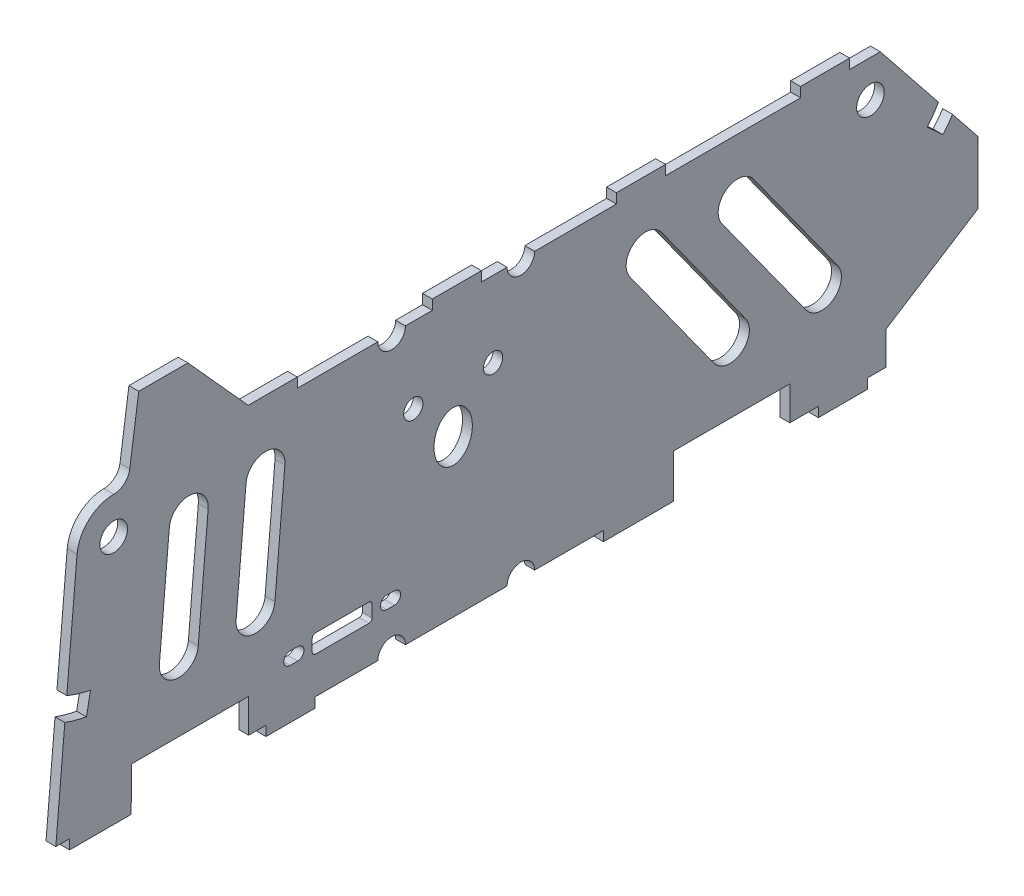
SolidWorks part; units mm, degrees
ref_plane "前视基准面" through (0, 0, 0) normal (0, 0, 1) x (1, 0, 0)
ref_plane "上视基准面" through (0, 0, 0) normal (0, 1, 0) x (1, 0, 0)
ref_plane "右视基准面" through (0, 0, 0) normal (1, 0, 0) x (0, 0, -1)
sketch "右侧结构" plane through (0, 0, 0) normal (1, 0, 0) x (0, 0, -1)
  line L0 (-44.2613, 14.3381) -> (-20.3822, 14.3381) construction
  line L1 (-96.6617, 0) -> (38.5883, 0)
  line L6 (-44.2613, 18.3959) -> (-20.3822, 18.3959) construction
  line L8 (-44.2613, 18.3959) -> (-44.2613, 16.3959) construction
  line L9 (-44.2613, 12.3381) -> (-20.3822, 12.3381) construction
  line L10 (-20.3822, 12.3381) -> (-20.3822, 14.3381) construction
  line L11 (-44.2613, 16.3959) -> (-20.3822, 16.3959) construction
  line L12 (-44.2613, 14.3381) -> (-44.2613, 12.3381) construction
  line L13 (-20.3822, 16.3959) -> (-20.3822, 18.3959) construction
  line L16 (-19.1356, 10.5554) -> (-5.2617, 10.5554) construction
  line L17 (-5.2617, 10.5554) -> (-5.2617, 14.5) construction
  line L18 (-5.2617, 14.5) -> (-19.1356, 14.5) construction
  line L19 (-19.1356, 14.5) -> (-19.1356, 10.5554) construction
  line L21 (36.0883, 39) -> (47.8781, 28.2124) construction
  line L22 (37.6933, 45) -> (-87.2267, 45)
  line L23 (-93.2039, 39.5229) -> (-96.6617, 0) construction
  line L25 (38.5883, 0) -> (38.5883, 43.8804) construction
  line L26 (38.5883, 43.8804) -> (37.6933, 45) construction
  line L36 (45.3288, 30.545) -> (47.8781, 28.2124)
  line L39 (-87.2267, 39) -> (-91.6701, 15.8134) construction
  line L42 (-91.0113, 19.2508) -> (-91.6701, 15.8134)
  line L45 (-93.2039, 39.5229) -> (-94.8767, 20.4034)
  line L57 (38.5883, 43.8804) -> (53.614, 25.0824) construction
  line L60 (53.614, 25.0824) -> (53.614, 14.8778)
  line L66 (38.5883, 5.3637) -> (38.5883, 0)
  line L88 (37.6933, 45) -> (47.164, 33.1517)
  line L97 (42.0237, 27.9708) -> (34.3307, 37.5952) construction
  line L107 (49.4706, 30.266) -> (53.614, 25.0824)
  line L108 (53.614, 14.8778) -> (38.5883, 5.3637)
  line L109 (42.0237, 27.9708) -> (44.209, 25.2369) construction
  line L110 (-95.194, 16.7764) -> (-96.6617, 0)
  arc A0 (-87.2267, 45) -> (-93.2039, 39.5229) centre (-87.2267, 39) ccw
  circle A21 centre (36.0883, 39) radius 2.25
  arc A23 (47.164, 33.1517) -> (42.0237, 27.9708) centre (36.0883, 39) cw construction
  arc A24 (49.4706, 30.266) -> (44.209, 25.2369) centre (36.0883, 39) cw construction
  arc A25 (47.164, 33.1517) -> (45.3288, 30.545) centre (36.0883, 39) cw
  arc A28 (49.4706, 30.266) -> (47.8781, 28.2124) centre (36.0883, 39) cw
  circle A31 centre (-87.2267, 39) radius 2.25
  arc A32 (-94.8767, 20.4034) -> (-91.0113, 19.2508) centre (-87.2267, 39) ccw
  arc A33 (-95.194, 16.7764) -> (-91.6701, 15.8134) centre (-87.2267, 39) ccw
  arc A34 (-44.1822, 45) -> (-39.6822, 45) centre (-41.9322, 45) ccw
  arc A35 (-23.1322, 45) -> (-18.6322, 45) centre (-20.8822, 45) ccw
  arc A37 (-44.1822, 0) -> (-39.6822, 0) centre (-41.9322, 0) cw
  arc A38 (-23.1322, 0) -> (-18.6322, 0) centre (-20.8822, 0) cw
  dimension "D1" = 6
  dimension "D3" = 12.3381
  dimension "D11" = 135.25
  dimension "D13" = 4.5
  dimension "D14" = 6
  dimension "D19" = 3.5
  dimension "D20" = 2.25
  dimension "D2" = 45
  dimension "D4" = 1.7827
  dimension "D5" = 3.9446
  dimension "D6" = 23.8791
  dimension "D7" = 13.8739
  dimension "D8" = 1.2466
  dimension "D9" = 2.0578
  dimension "D10" = 2
  dimension "D12" = 85
  dimension "D15" = 43.85
  dimension "D16" = 3.5
  dimension "D17" = 5
  dimension "D18" = 2.5
  dimension "D21" = 21.55
  dimension "D22" = 0.5
extrude "凸台-拉伸1" add sketch "右侧结构" along normal blind 1.6
sketch "草图2" plane through (0, 0, 0) normal (1, 0, 0) x (0, 0, -1)
  line L0 (35.5883, 0) -> (35.5883, -1.6)
  line L1 (-83.1502, 57.5) -> (-84.6077, 47.2723)
  line L2 (35.5883, -1.6) -> (27.5883, -1.6)
  line L3 (27.5883, -1.6) -> (27.5883, 0)
  line L4 (27.5883, 0) -> (35.5883, 0)
  line L5 (-83.1502, 57.5) -> (-75.1391, 57.5)
  line L6 (-2.4117, 0) -> (5.5883, 0)
  line L7 (5.5883, 0) -> (5.5883, -1.6)
  line L8 (5.5883, -1.6) -> (-2.4117, -1.6)
  line L9 (-2.4117, -1.6) -> (-2.4117, 0)
  line L10 (-32.4117, 0) -> (-24.4117, 0) construction
  line L11 (-24.4117, 0) -> (-24.4117, -1.6) construction
  line L12 (-24.4117, -1.6) -> (-32.4117, -1.6) construction
  line L13 (-32.4117, -1.6) -> (-32.4117, 0) construction
  line L14 (-62.4117, 0) -> (-54.4117, 0)
  line L15 (-54.4117, 0) -> (-54.4117, -1.6)
  line L16 (-54.4117, -1.6) -> (-62.4117, -1.6)
  line L17 (-62.4117, -1.6) -> (-62.4117, 0)
  line L18 (-92.4117, 0) -> (-84.4117, 0)
  line L19 (-84.4117, 0) -> (-84.4117, -1.6)
  line L20 (-84.4117, -1.6) -> (-92.4117, -1.6)
  line L21 (-92.4117, -1.6) -> (-92.4117, 0)
  line L22 (32.6933, 46.6) -> (32.6933, 45)
  line L23 (32.6933, 45) -> (24.6933, 45)
  line L24 (24.6933, 45) -> (24.6933, 46.6)
  line L25 (24.6933, 46.6) -> (32.6933, 46.6)
  line L26 (-75.1391, 57.5) -> (-65.3067, 46.6)
  line L27 (2.6933, 46.6) -> (2.6933, 45)
  line L28 (2.6933, 45) -> (-5.3067, 45)
  line L29 (-5.3067, 45) -> (-5.3067, 46.6)
  line L30 (-5.3067, 46.6) -> (2.6933, 46.6)
  line L31 (-27.3067, 46.6) -> (-27.3067, 45)
  line L32 (-27.3067, 45) -> (-35.3067, 45)
  line L33 (-35.3067, 45) -> (-35.3067, 46.6)
  line L34 (-35.3067, 46.6) -> (-27.3067, 46.6)
  line L35 (-57.3067, 46.6) -> (-57.3067, 45)
  line L36 (-57.3067, 45) -> (-65.3067, 45)
  line L37 (-65.3067, 45) -> (-65.3067, 46.6) construction
  line L38 (-65.3067, 46.6) -> (-57.3067, 46.6)
  line L39 (38.5883, 5.3637) -> (38.5883, 0) construction
  line L40 (-18.6322, 0) -> (38.5883, 0) construction
  line L41 (37.6933, 45) -> (-18.6322, 45) construction
  line L42 (-87.2267, 45) -> (-65.3067, 45)
  arc A0 (-87.2267, 45) -> (-84.6077, 47.2723) centre (-87.2267, 47.6455) ccw
  dimension "D1" = 3
  dimension "D2" = 1.6
  dimension "D3" = 8
  dimension "D5" = 1.6
  dimension "D6" = 8
  dimension "D7" = 5
  dimension "D9" = 12.5
  dimension "D4" = 5
  dimension "D8" = 4
extrude "上下板接口" add sketch "草图2" along normal up to surface (1.6 mm away) from surface at 0 up to face at (1.6, 39, 84.9767) starting at face at (0, 39, 84.9767)
sketch "Sketch2" plane through (1.6, 0, 0) normal (1, 0, 0) x (0, 0, -1)
  line L0 (-84.3141, 0) -> (-84.3141, 5.5)
  line L1 (-84.4117, 0) -> (-62.4117, 0) construction
  line L2 (-84.3141, 5.5) -> (-65.2413, 5.5)
  line L3 (-65.2413, 5.5) -> (-65.2413, 0)
  line L4 (-65.2413, 0) -> (-84.3141, 0)
  line L5 (3.9897, 0) -> (3.9897, 5.5)
  line L6 (5.5883, 0) -> (27.5883, 0) construction
  line L7 (3.9897, 5.5) -> (22.9457, 5.5)
  line L8 (22.9457, 5.5) -> (22.9457, 0)
  line L9 (22.9457, 0) -> (3.9897, 0)
  line L10 (22.9457, 0) -> (22.9457, -4.1)
  line L11 (22.9457, -4.1) -> (3.9897, -4.1)
  line L12 (3.9897, -4.1) -> (3.9897, 0)
  line L13 (-65.2413, 0) -> (-65.2413, -5.2387)
  line L14 (-65.2413, -5.2387) -> (-84.3141, -5.2387)
  line L15 (-84.3141, -5.2387) -> (-84.3141, 0)
  line L16 (5.5883, -1.6) -> (-2.4117, -1.6) construction
  point P12 (0, 0)
  point P17 (0, 0)
  point P19 (0, 0)
  point P21 (0, 0)
  point P23 (0, 0)
  point P24 (0, 0)
  point P26 (0, 0)
  point P28 (0, 0)
  point P29 (0, 0)
  point P30 (0, 0)
  point P31 (0, 0)
  point P32 (0, 0)
  dimension "D1" = 5.5
  dimension "D2" = 65.2413
  dimension "D3" = 19.0729
  dimension "D4" = 3.9897
  dimension "D5" = 18.956
  dimension "D6" = 2.5
extrude "侧板连接件让位" cut sketch "Sketch2" against normal through all contours L4 L3 L2 L0 | L15 L14 L13 L4 | L9 L8 L7 L5 | L12 L11 L10 L9
sketch "天线接口-草图" plane through (1.6, 0, 0) normal (1, 0, 0) x (0, 0, -1)
  line L0 (38.5883, 0) -> (-117.1754, 0) construction
  line L1 (38.5883, -1000) -> (38.5883, 49000) construction
  line L2 (-38.4117, 32.6514) -> (-25.4117, 32.6514) construction
  line L3 (-31.9117, 25.5) -> (-31.9117, 32.6514) construction
  circle A7 centre (-38.4117, 32.6514) radius 1.575
  circle A8 centre (-25.4117, 32.6514) radius 1.575
  ellipse E0 centre (-31.9117, 25.5) end of major axis (-31.9117, 29.5794) minor radius 3.125
  dimension "D1" = 3.15
  dimension "D2" = 3.125
  dimension "D3" = 3.072
  dimension "D4" = 4.0794
  dimension "D5" = 13
  dimension "D6" = 70.5
  dimension "D7" = 25.5
extrude "天线接口" cut sketch "天线接口-草图" against normal through all
sketch "草图3" plane through (1.6, 0, 0) normal (1, 0, 0) x (0, 0, -1)
  line L0 (-75, 35.5) -> (-76.6185, 17) construction
  line L1 (-71.8371, 35.2233) -> (-73.4556, 16.7233)
  line L2 (-78.1629, 35.7767) -> (-79.7815, 17.2767)
  line L3 (-93.2039, 39.5229) -> (-94.8767, 20.4034) construction
  line L6 (14.45, 35.5) -> (28.1799, 16.428) construction
  line L7 (17.0267, 37.355) -> (30.7566, 18.283)
  line L8 (11.8733, 33.645) -> (25.6031, 14.573)
  line L9 (-0.55, 35.5) -> (13.1799, 16.428) construction
  line L12 (2.0267, 37.355) -> (15.7566, 18.283)
  line L13 (-3.1267, 33.645) -> (10.6031, 14.573)
  line L14 (14.45, 35.5) -> (-0.55, 35.5) construction
  line L15 (14.45, 35.5) -> (34.8658, 35.5) construction
  line L16 (-62.5, 35.5) -> (-64.1185, 17) construction
  line L17 (-59.3371, 35.2233) -> (-60.9556, 16.7233)
  line L18 (-65.6629, 35.7767) -> (-67.2815, 17.2767)
  line L19 (-75, 35.5) -> (-62.5, 35.5) construction
  arc A0 (-71.8371, 35.2233) -> (-78.1629, 35.7767) centre (-75, 35.5) ccw
  arc A1 (-79.7815, 17.2767) -> (-73.4556, 16.7233) centre (-76.6185, 17) ccw
  arc A4 (17.0267, 37.355) -> (11.8733, 33.645) centre (14.45, 35.5) ccw
  arc A5 (25.6031, 14.573) -> (30.7566, 18.283) centre (28.1799, 16.428) ccw
  arc A8 (2.0267, 37.355) -> (-3.1267, 33.645) centre (-0.55, 35.5) ccw
  arc A9 (10.6031, 14.573) -> (15.7566, 18.283) centre (13.1799, 16.428) ccw
  arc A10 (-59.3371, 35.2233) -> (-65.6629, 35.7767) centre (-62.5, 35.5) ccw
  arc A11 (-67.2815, 17.2767) -> (-60.9556, 16.7233) centre (-64.1185, 17) ccw
  point P2 (-75.8093, 26.25)
  point P11 (21.3149, 25.964)
  point P20 (6.3149, 25.964)
  point P30 (-63.3093, 26.25)
  dimension "D3" = 3.175
  dimension "D2" = 15
  dimension "D4" = 35.5
  dimension "D5" = 14.45
  dimension "D6" = 54.25
  dimension "D7" = 23.5
  dimension "D8" = 18.5
  dimension "D9" = 75
  dimension "D11" = 12.5
  dimension "D1" = 2
  dimension "D10" = 2
extrude "通风口-兼具天线捆扎功能" cut sketch "草图3" against normal through all
sketch "Sketch1" plane through (0, 0, 0) normal (1, 0, 0) x (0, 0, -1)
  line L0 (-54.375, 9) -> (-45.625, 9)
  line L1 (-54.875, 8.5) -> (-54.875, 6.5)
  line L2 (-50, 9) -> (-50, -9.6698) construction
  line L3 (-45.125, 8.5) -> (-45.125, 6.5)
  line L4 (-54.875, 7.5) -> (-50, 7.5) construction
  line L5 (-54.375, 6) -> (-45.625, 6)
  line L8 (-57.25, 7.5) -> (-58.5, 7.5) construction
  line L9 (-57.25, 6.475) -> (-58.5, 6.475)
  line L10 (-57.25, 8.525) -> (-58.5, 8.525)
  line L11 (-42.75, 7.5) -> (-41.5, 7.5) construction
  line L12 (-42.75, 6.475) -> (-41.5, 6.475)
  line L13 (-42.75, 8.525) -> (-41.5, 8.525)
  circle A0 centre (-57.25, 7.5) radius 1.025 construction
  circle A1 centre (-42.75, 7.5) radius 1.025 construction
  arc A2 (-54.875, 8.5) -> (-54.375, 9) centre (-54.375, 8.5) cw
  arc A3 (-54.875, 6.5) -> (-54.375, 6) centre (-54.375, 6.5) ccw
  arc A4 (-45.125, 8.5) -> (-45.625, 9) centre (-45.625, 8.5) ccw
  arc A5 (-45.125, 6.5) -> (-45.625, 6) centre (-45.625, 6.5) cw
  arc A6 (-57.25, 6.475) -> (-57.25, 8.525) centre (-57.25, 7.5) ccw
  arc A7 (-58.5, 8.525) -> (-58.5, 6.475) centre (-58.5, 7.5) ccw
  arc A8 (-42.75, 6.475) -> (-42.75, 8.525) centre (-42.75, 7.5) cw
  arc A9 (-41.5, 8.525) -> (-41.5, 6.475) centre (-41.5, 7.5) cw
  point P17 (-57.875, 7.5)
  point P32 (-42.125, 7.5)
  dimension "D2" = 2.05
  dimension "D7" = 0.5
  dimension "D1" = 9.75
  dimension "D3" = 3
  dimension "D4" = 14.5
  dimension "D5" = 50
  dimension "D6" = 7.5
  dimension "D8" = 1.25
extrude "USB-C供电接口" cut sketch "Sketch1" along normal through all
sketch "Sketch3" plane through (1.6, 0, 0) normal (1, 0, 0) x (0, 0, -1)
  line L0 (-92.4117, -1.6) -> (-94.4117, -1.6)
  line L1 (-94.4117, -1.6) -> (-94.4117, 0)
  line L2 (-96.6617, 0) -> (-92.4117, 0) construction
  line L3 (-94.4117, 0) -> (-92.4117, 0) construction
  line L4 (-92.4117, 0) -> (-92.4117, -1.6) construction
  line L5 (-92.1617, -1.6) -> (-92.1617, 0.25)
  line L6 (-84.4117, -1.6) -> (-92.4117, -1.6) construction
  line L7 (-92.1617, 0.25) -> (-94.4117, 0.25)
  line L8 (-94.4117, 0.25) -> (-94.4117, 0)
  line L9 (-2.4117, -1.6) -> (-7.4117, -1.6)
  line L10 (-7.4117, -1.6) -> (-7.4117, 0)
  line L11 (-18.6322, 0) -> (-2.4117, 0) construction
  line L12 (-7.4117, 0) -> (-7.4117, 0.25)
  line L13 (-7.4117, 0.25) -> (-2.1617, 0.25)
  line L14 (-2.1617, 0.25) -> (-2.1617, -1.6)
  line L15 (3.9897, -1.6) -> (-2.4117, -1.6) construction
  line L16 (-2.1617, -1.6) -> (-2.4117, -1.6)
  line L17 (-2.4117, 0) -> (-2.4117, -1.6) construction
  line L18 (-7.4117, 0) -> (-2.4117, 0) construction
  line L19 (-92.4117, -1.6) -> (-92.1617, -1.6)
  point P12 (-92.4117, -0.8)
  dimension "D1" = 2
  dimension "D2" = 0.25
  dimension "D3" = 0.25
  dimension "D4" = 0.25
  dimension "D5" = 5
extrude "Boss-Extrude1" add sketch "Sketch3" against normal up to surface (1.6 mm away) from surface at 0 up to face at (0, 7.5, 57.875) starting at face at (1.6, 26.25, 75.8093)
